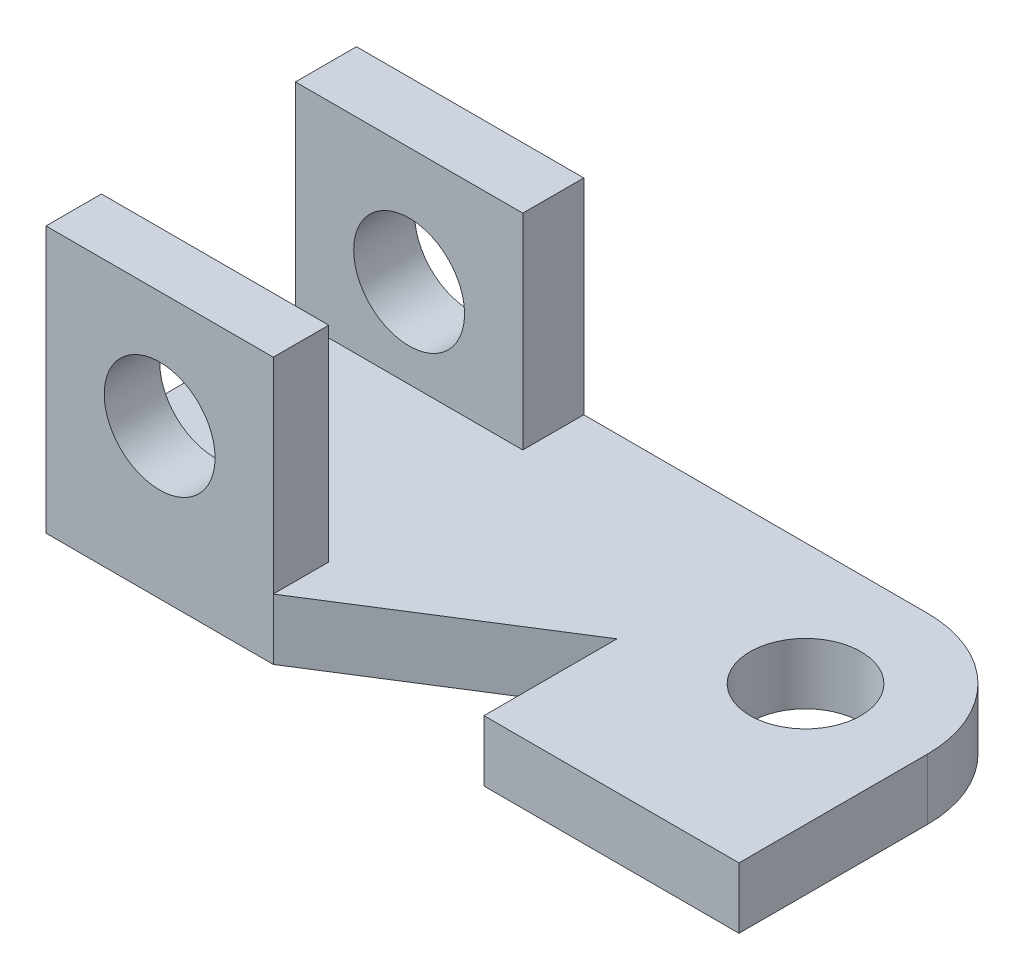
SolidWorks part; units mm, degrees
ref_plane "Front Plane" through (0, 0, 0) normal (0, 0, 1) x (1, 0, 0)
ref_plane "Top Plane" through (0, 0, 0) normal (0, 1, 0) x (1, 0, 0)
ref_plane "Right Plane" through (0, 0, 0) normal (1, 0, 0) x (0, 0, -1)
sketch "Sketch1" plane through (0, 0, 0) normal (0, 1, 0) x (1, 0, 0)
  line L0 (0, 0) -> (-46, 0)
  line L1 (-46, 0) -> (-46, 24)
  line L2 (-46, 24) -> (-84, 0)
  line L3 (-84, 0) -> (-125, 0)
  line L4 (-125, 0) -> (-125, 56)
  line L5 (-125, 56) -> (-22, 56)
  line L6 (0, 34) -> (0, 0)
  arc A0 (-22, 56) -> (0, 34) centre (-22, 34) cw
  circle A1 centre (-22, 34) radius 10
  dimension "D5" = 22
  dimension "D7" = 20
  dimension "D1" = 56
  dimension "D2" = 125
  dimension "D3" = 38
  dimension "D4" = 24
  dimension "D6" = 41
extrude "Boss-Extrude1" add sketch "Sketch1" along normal blind 11
sketch "Sketch3" plane through (0, 11, 0) normal (0, 1, 0) x (1, 0, 0)
  line L0 (-125, 0) -> (-84, 0)
  line L1 (-84, 0) -> (-84, 10)
  line L2 (-84, 10) -> (-125, 10)
  line L3 (-125, 56) -> (-125, 0) construction
  line L4 (-125, 10) -> (-125, 0)
  dimension "D1" = 10
extrude "Boss-Extrude2" add sketch "Sketch3" along normal blind 37
sketch "Sketch4" plane through (0, 0, 0) normal (0, 0, 1) x (1, 0, 0)
  line L0 (-125, 0) -> (-84, 0) construction
  line L1 (-125, 48) -> (-125, 0) construction
  circle A0 centre (-104.5, 27) radius 10
  dimension "D3" = 20
  dimension "D1" = 27
  dimension "D2" = 20.5
extrude "Cut-Extrude1" cut sketch "Sketch4" against normal blind 37
sketch "Sketch5" plane through (0, 0, -56) normal (0, 0, -1) x (-1, 0, 0)
  line L0 (84, 11) -> (125, 11)
  line L1 (22, 11) -> (125, 11) construction
  line L2 (84, 11) -> (125, 11) construction
  line L3 (125, 11) -> (125, 48)
  line L4 (125, 48) -> (84, 48)
  line L5 (84, 48) -> (125, 48) construction
  line L6 (84, 48) -> (84, 11)
  circle A0 centre (104.5, 27) radius 10
extrude "Boss-Extrude3" add sketch "Sketch5" against normal blind 11
